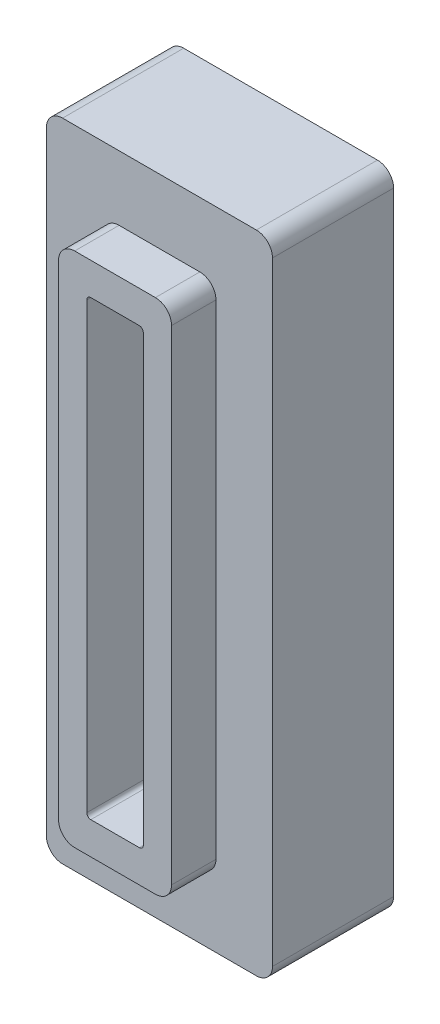
SolidWorks part; units mm, degrees
ref_plane "Спереди" through (0, 0, 0) normal (0, 0, 1) x (1, 0, 0)
ref_plane "Сверху" through (0, 0, 0) normal (0, 1, 0) x (1, 0, 0)
ref_plane "Справа" through (0, 0, 0) normal (1, 0, 0) x (0, 0, -1)
sketch "Sketch1" plane through (0, 0, 0) normal (0, 0, 1) x (1, 0, 0)
  line L1 (-7, -20) -> (7, -20)
  line L2 (-7, -20) -> (-7, 20)
  line L3 (-7, 20) -> (7, 20)
  line L4 (7, -20) -> (7, 20)
  line L5 (-7, -20) -> (7, 20) construction
  line L6 (-7, 20) -> (7, -20) construction
  line L7 (-1.75, -14) -> (1.75, -14)
  line L8 (-1.75, -14) -> (-1.75, 14)
  line L9 (-1.75, 14) -> (1.75, 14)
  line L10 (1.75, -14) -> (1.75, 14)
  line L11 (-1.75, -14) -> (1.75, 14) construction
  line L12 (-1.75, 14) -> (1.75, -14) construction
  point P0 (0, 0)
  point P6 (0, 0)
  dimension "D1" = 14
  dimension "D2" = 40
  dimension "D3" = 28
  dimension "D4" = 3.5
extrude "Extrude1" add sketch "Sketch1" along normal blind 1.5
sketch "Sketch2" plane through (0, 0, 1.5) normal (0, 0, 1) x (1, 0, 0)
  line L0 (-1.75, -14) -> (1.75, -14) construction
  line L1 (-1.75, 14) -> (-1.75, -14) construction
  line L2 (1.75, 14) -> (-1.75, 14) construction
  line L3 (1.75, -14) -> (1.75, 14) construction
  line L4 (-1.75, -14) -> (1.75, -14)
  line L5 (-1.75, 14) -> (-1.75, -14)
  line L6 (1.75, 14) -> (-1.75, 14)
  line L7 (1.75, -14) -> (1.75, 14)
  line L9 (-3.5, -16) -> (3.5, -16)
  line L10 (-3.5, -16) -> (-3.5, 16)
  line L11 (-3.5, 16) -> (3.5, 16)
  line L12 (3.5, -16) -> (3.5, 16)
  line L13 (-3.5, -16) -> (3.5, 16) construction
  line L14 (-3.5, 16) -> (3.5, -16) construction
  point P3 (0, 0)
  dimension "D1" = 7
  dimension "D2" = 32
extrude "Extrude2" add sketch "Sketch2" along normal blind 2.75
sketch "Sketch3" plane through (0, 0, 0) normal (0, 0, -1) x (-1, 0, 0)
  line L1 (-4.9, -17.7) -> (4.9, -17.7)
  line L2 (-4.9, -17.7) -> (-4.9, 17.7)
  line L3 (-4.9, 17.7) -> (4.9, 17.7)
  line L4 (-7, 20) -> (-7, -20)
  line L5 (-7, -20) -> (7, -20)
  line L6 (7, -20) -> (7, 20)
  line L7 (7, 20) -> (-7, 20)
  line L8 (-7, 20) -> (-7, -20)
  line L9 (-7, -20) -> (7, -20)
  line L10 (7, -20) -> (7, 20)
  line L11 (7, 20) -> (-7, 20)
  line L12 (4.9, -17.7) -> (4.9, 17.7)
  line L13 (-4.9, -17.7) -> (4.9, 17.7) construction
  line L14 (-4.9, 17.7) -> (4.9, -17.7) construction
  point P2 (0, 0)
  dimension "D2" = 9.8
  dimension "D3" = 35.4
  dimension "D1" = 0
extrude "Extrude3" add sketch "Sketch3" along normal blind 6
fillet "Fillet1" radius 0.25 8 edges at (1.75, 14, 2.125) (-1.75, 14, 2.125) (-1.75, -14, 2.125) (1.75, -14, 2.125) (4.9, -17.7, -3) (-4.9, -17.7, -3) (-4.9, 17.7, -3) (4.9, 17.7, -3)
fillet "Fillet2" radius 1 8 edges at (3.5, -16, 2.875) (-3.5, -16, 2.875) (3.5, 16, 2.875) (-3.5, 16, 2.875) (-7, 20, -2.25) (-7, -20, -2.25) (7, -20, -2.25) (7, 20, -2.25)
